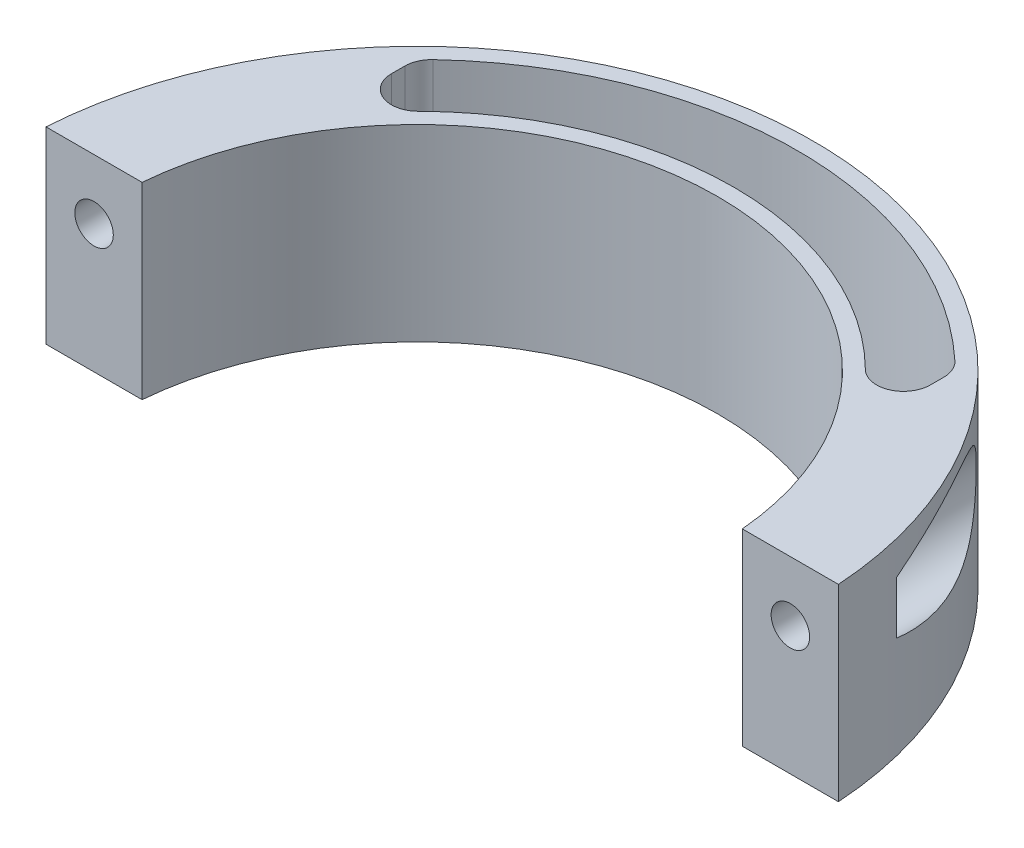
SolidWorks part; units mm, degrees
ref_plane "Front Plane" through (0, 0, 0) normal (0, 0, 1) x (1, 0, 0)
ref_plane "Top Plane" through (0, 0, 0) normal (0, 1, 0) x (1, 0, 0)
ref_plane "Right Plane" through (0, 0, 0) normal (1, 0, 0) x (0, 0, -1)
sketch "Sketch1" plane through (0, 0, 0) normal (0, 1, 0) x (1, 0, 0)
  circle A0 centre (0, 0) radius 57.15 construction
  circle A1 centre (0, 0) radius 73.66
  circle A2 centre (0, 0) radius 55.88
  dimension "D1" = 114.3
  dimension "D2" = 1.27
  dimension "D3" = 17.78
extrude "Boss-Extrude1" add sketch "Sketch1" along normal blind 22.225
sketch "Sketch3" plane through (0, 22.225, 0) normal (0, 1, 0) x (1, 0, 0)
  line L0 (-55, 0) -> (55, 0) construction
  line L1 (-87.1123, 4.7625) -> (87.0672, 4.7625)
  line L2 (-87.1123, 4.7625) -> (-87.1123, -90.3663)
  line L3 (-87.1123, -90.3663) -> (87.0672, -90.3663)
  line L4 (87.0672, 4.7625) -> (87.0672, -90.3663)
  dimension "D1" = 4.7625
extrude "Cut-Extrude1" cut sketch "Sketch3" against normal up to next
hole_wizard "1/4 Clearance Hole1" positions "3DSketch1" profile "Sketch4" hole size "1/4" standard "ANSI Inch" end condition up to next
sketch3d "3DSketch1"
  line L0 (-73.5059, 22.225, -4.7625) -> (-55.6767, 0, -4.7625) construction
  line L2 (55.6767, 22.225, -4.7625) -> (73.5059, 0, -4.7625) construction
  point P0 (-64.5913, 11.1125, -4.7625)
  point P2 (64.5913, 11.1125, -4.7625)
sketch "Sketch4" plane through (-64.5913, 11.1125, -4.7625) normal (1, 0, 0) x (0, -1, 0)
  line L0 (0, 0) -> (0, 30.646)
  line L1 (0, 30.646) -> (3.5712, 30.646)
  line L2 (3.5712, 30.646) -> (3.5712, 0)
  line L5 (3.5712, 0) -> (0, 0)
  line L11 (0, -6.35) -> (0, 107.95) construction
  dimension "Thru Hole Dia." = 7.1425
  dimension "Thru Hole Depth" = 30.646
ref_plane "Plane1" through (0, 0, -73.66) normal (0, 0, -1) x (-1, 0, 0)
sketch "Sketch5" plane through (0, 0, -73.66) normal (0, 0, -1) x (-1, 0, 0)
  circle A0 centre (-64.5913, 11.1125) radius 3.5712 construction
  circle A1 centre (-64.5913, 11.1125) radius 3.5712 construction
  circle A2 centre (64.5913, 11.1125) radius 3.5712 construction
  circle A3 centre (64.5913, 11.1125) radius 3.5712 construction
  circle A4 centre (-64.5913, 11.1125) radius 8.5
  circle A5 centre (64.5913, 11.1125) radius 8.5
  dimension "D1" = 17
extrude "Cut-Extrude2" cut sketch "Sketch5" against normal offset from surface (56.1975 mm away) 12.7 up to face at (-61.02, 11.1125, -4.7625)
sketch "Sketch7" plane through (0, 0, 0) normal (0, -1, 0) x (1, 0, 0)
  line L2 (73.5059, -4.7625) -> (55.6767, -4.7625)
  line L3 (-55.6767, -4.7625) -> (-73.5059, -4.7625)
  line L4 (73.5059, -4.7625) -> (55.6767, -4.7625)
  line L5 (-55.6767, -4.7625) -> (-73.5059, -4.7625)
  arc A2 (-73.5059, -4.7625) -> (73.5059, -4.7625) centre (0, 0) ccw
  arc A3 (-55.6767, -4.7625) -> (55.6767, -4.7625) centre (0, 0) ccw
  arc A4 (-73.5059, -4.7625) -> (73.5059, -4.7625) centre (0, 0) ccw
  arc A5 (-55.6767, -4.7625) -> (55.6767, -4.7625) centre (0, 0) ccw
  dimension "D1" = 0
extrude "Boss-Extrude3" add sketch "Sketch7" along normal blind 12.7
sketch "Sketch9" plane through (0, 22.225, 0) normal (0, 1, 0) x (1, 0, 0)
  line L2 (-50, 49.9283) -> (-50, 31.0943)
  line L3 (50, 49.9283) -> (50, 31.0943)
  line L4 (58.3661, 7.7625) -> (70.2323, 7.7625)
  line L5 (-70.2323, 7.7625) -> (-58.3661, 7.7625)
  line L8 (0, -12.2237) -> (0, 12.2237) construction
  arc A4 (70.2323, 7.7625) -> (-70.2323, 7.7625) centre (0, 0) ccw
  arc A5 (58.3661, 7.7625) -> (-58.3661, 7.7625) centre (0, 0) ccw
  arc A6 (50, 49.9283) -> (-50, 49.9283) centre (0, 0) ccw
  arc A7 (50, 31.0943) -> (-50, 31.0943) centre (0, 0) ccw
  dimension "D2" = 50
  dimension "D3" = 50
  dimension "D1" = 3
extrude "Cut-Extrude3" cut sketch "Sketch9" against normal offset from surface (31.925 mm away) 3 up to face at (0, -12.7, -34.7662)
fillet "Fillet1" radius 5 4 edges at (50, 6.2625, -31.0943) (50, 6.2625, -49.9283) (-50, 6.2625, -31.0943) (-50, 6.2625, -49.9283)
equation "\"D3@Sketch9\"=\"D2@Sketch9\""
